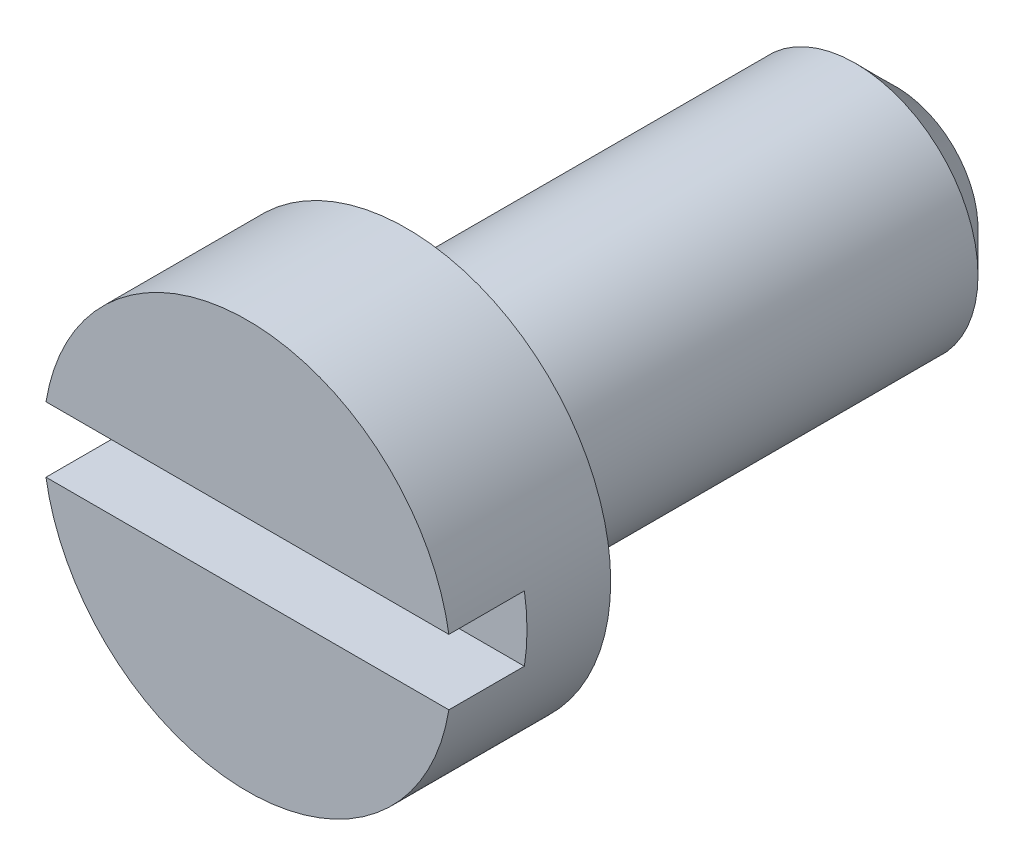
SolidWorks part; units mm, degrees
ref_plane "Спереди" through (0, 0, 0) normal (0, 0, 1) x (1, 0, 0)
ref_plane "Сверху" through (0, 0, 0) normal (0, 1, 0) x (1, 0, 0)
ref_plane "Справа" through (0, 0, 0) normal (1, 0, 0) x (0, 0, -1)
sketch "Эскиз12" plane through (0, 0, 0) normal (0, 0, 1) x (1, 0, 0)
  circle A0 centre (0, 0) radius 5
extrude "Вытянуть3" add sketch "Эскиз12" along normal blind 3.9
sketch "Эскиз13" plane through (0, 0, 0) normal (0, 0, -1) x (-1, 0, 0)
  circle A0 centre (0, 0) radius 3
extrude "Вытянуть4" add sketch "Эскиз13" along normal blind 12
sketch "Эскиз14" plane through (0, 0, 3.9) normal (0, 0, 1) x (1, 0, 0)
  line L0 (-5, 0) -> (5, 0) construction
  circle A0 centre (0, 0) radius 5 construction
sketch "Эскиз20" plane through (0, 0, 3.9) normal (0, 0, 1) x (1, 0, 0)
  line L0 (-5, 0) -> (5, 0) construction
  line L1 (-5.2723, 0.8) -> (5.4093, 0.8)
  line L2 (-5.2723, 0.8) -> (-5.2723, -0.8)
  line L3 (-5.2723, -0.8) -> (5.4093, -0.8)
  line L4 (5.4093, 0.8) -> (5.4093, -0.8)
  dimension "D1" = 0.8
  dimension "D2" = 0.8
extrude "Вырез-Вытянуть8" cut sketch "Эскиз20" against normal blind 1.85
chamfer "Фаска1" distance 1 angle 45 1 edges at (-3, 0, -12)
